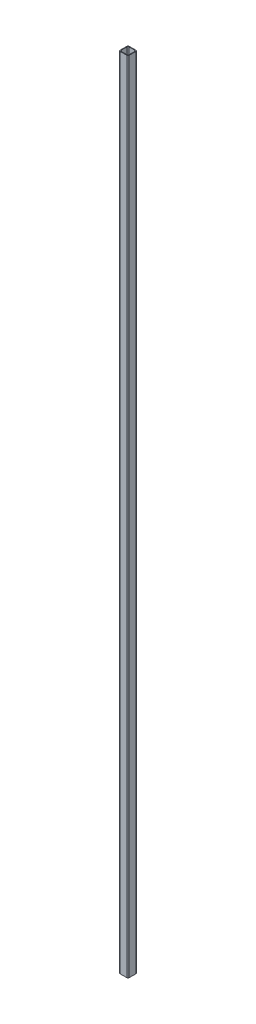
SolidWorks part; units mm, degrees
material "Hexcel AS4C (3000 Filaments)"
ref_plane "Front Plane" through (0, 0, 0) normal (0, 0, 1) x (1, 0, 0)
ref_plane "Top Plane" through (0, 0, 0) normal (0, 1, 0) x (1, 0, 0)
ref_plane "Right Plane" through (0, 0, 0) normal (1, 0, 0) x (0, 0, -1)
sketch "Sketch1" plane through (0, 0, 0) normal (0, 1, 0) x (1, 0, 0)
  line L1 (-3, -4) -> (3, -4)
  line L2 (-4, -3) -> (-4, 3)
  line L3 (-3, 4) -> (3, 4)
  line L4 (4, -3) -> (4, 3)
  line L5 (-4, -4) -> (4, 4) construction
  line L6 (-4, 4) -> (4, -4) construction
  line L7 (-2.5, -3.5) -> (2.5, -3.5)
  line L8 (-3.5, -2.5) -> (-3.5, 2.5)
  line L9 (-2.5, 3.5) -> (2.5, 3.5)
  line L10 (3.5, -2.5) -> (3.5, 2.5)
  line L11 (-3.5, -3.5) -> (3.5, 3.5) construction
  line L12 (-3.5, 3.5) -> (3.5, -3.5) construction
  arc A0 (-3, -4) -> (-4, -3) centre (-3, -3) cw
  arc A1 (3, 4) -> (4, 3) centre (3, 3) cw
  arc A2 (3, -4) -> (4, -3) centre (3, -3) ccw
  arc A3 (-4, 3) -> (-3, 4) centre (-3, 3) cw
  arc A4 (-2.5, -3.5) -> (-3.5, -2.5) centre (-2.5, -2.5) cw
  arc A5 (2.5, -3.5) -> (3.5, -2.5) centre (2.5, -2.5) ccw
  arc A6 (2.5, 3.5) -> (3.5, 2.5) centre (2.5, 2.5) cw
  arc A7 (-3.5, 2.5) -> (-2.5, 3.5) centre (-2.5, 2.5) cw
  point P0 (0, 0)
  point P18 (0, 0)
  dimension "D3" = 1
  dimension "D6" = 1
  dimension "D7" = 1
  dimension "D8" = 1
  dimension "D9" = 1
  dimension "D1" = 8
  dimension "D2" = 8
  dimension "D4" = 0.5
  dimension "D5" = 0.5
extrude "Boss-Extrude1" add sketch "Sketch1" along normal blind 715
